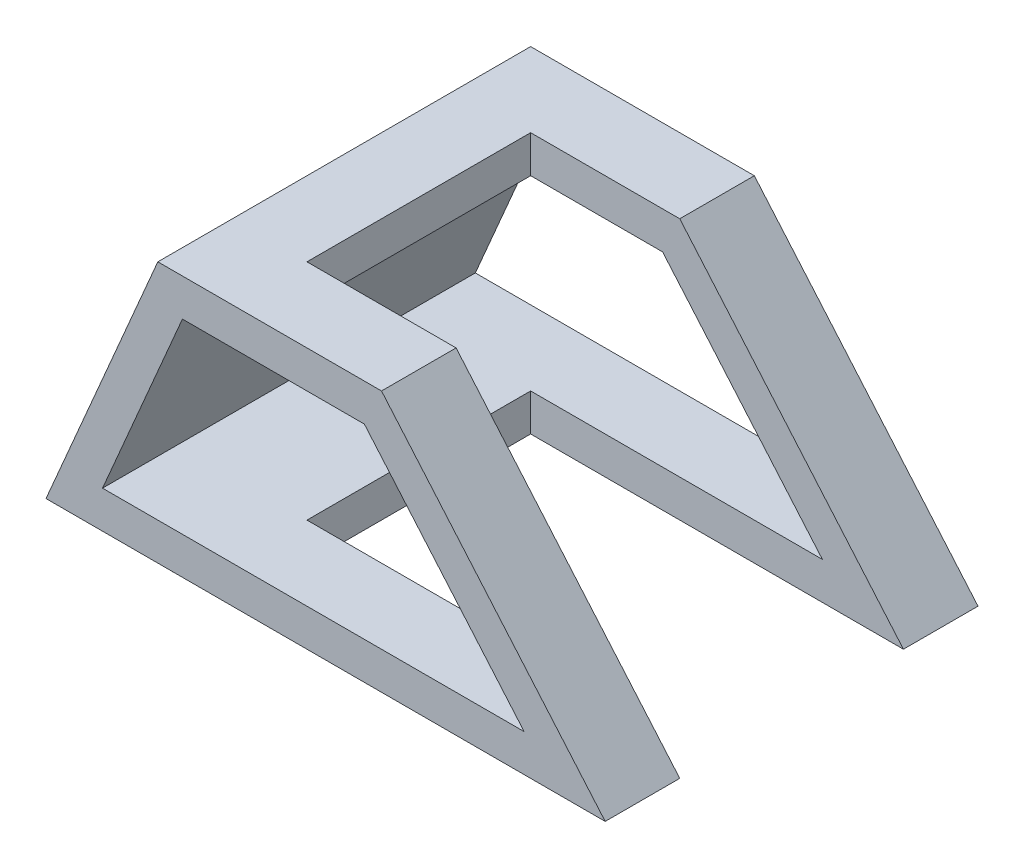
SolidWorks part; units mm, degrees
ref_plane "Plan de face" through (0, 0, 0) normal (0, 0, 1) x (1, 0, 0)
ref_plane "Plan de dessus" through (0, 0, 0) normal (0, 1, 0) x (1, 0, 0)
ref_plane "Plan de droite" through (0, 0, 0) normal (1, 0, 0) x (0, 0, -1)
sketch "Esquisse1" plane through (0, 0, 0) normal (0, 0, 1) x (1, 0, 0)
  line L0 (0, 0) -> (60, 0)
  line L1 (60, 0) -> (120, -70)
  line L2 (120, -70) -> (-30, -70)
  line L3 (-30, -70) -> (0, 0)
  dimension "D1" = 60
  dimension "D2" = 60
  dimension "D3" = 30
  dimension "D4" = 70
extrude "Boss.-Extru.1" add sketch "Esquisse1" along normal blind 100
sketch "Esquisse2" plane through (0, 0, 100) normal (0, 0, 1) x (1, 0, 0)
  line L0 (55.4007, -10) -> (6.594, -10)
  line L1 (55.4007, -10) -> (98.2578, -60)
  line L2 (-14.8346, -60) -> (98.2578, -60)
  line L3 (6.594, -10) -> (-14.8346, -60)
  line L4 (120, -70) -> (60, 0) construction
  line L5 (0, 0) -> (-30, -70) construction
  line L7 (60, 0) -> (0, 0) construction
  line L8 (-30, -70) -> (120, -70) construction
  dimension "D1" = 10
  dimension "D2" = 10
  dimension "D3" = 10
  dimension "D4" = 10
extrude "Enlèv. mat.-Extru.1" cut sketch "Esquisse2" against normal blind 100
sketch "Esquisse4" plane through (34.5882, 29.6471, 0) normal (0.7593, 0.6508, 0) x (0, 0, -1)
  line L0 (-80, -39.0475) -> (-20, -39.0475)
  line L1 (-100, -39.0475) -> (0, -39.0475) construction
  line L2 (-20, -39.0475) -> (-20, -131.2429)
  line L3 (-100, -131.2429) -> (0, -131.2429) construction
  line L4 (-20, -131.2429) -> (-80, -131.2429)
  line L5 (-80, -131.2429) -> (-80, -39.0475)
  line L6 (-100, -131.2429) -> (-100, -39.0475) construction
  dimension "D1" = 60
  dimension "D2" = 20
extrude "Enlèv. mat.-Extru.7" cut sketch "Esquisse4" against normal blind 60
sketch "Esquisse6" plane through (0, 0, 0) normal (0, 1, 0) x (1, 0, 0)
  line L0 (60, -20) -> (20, -20)
  line L1 (60, -80) -> (20, -80)
  line L2 (20, -80) -> (20, -20)
  line L3 (60, -20) -> (60, -80)
  dimension "D1" = 40
extrude "Enlèv. mat.-Extru.8" cut sketch "Esquisse6" against normal blind 120
